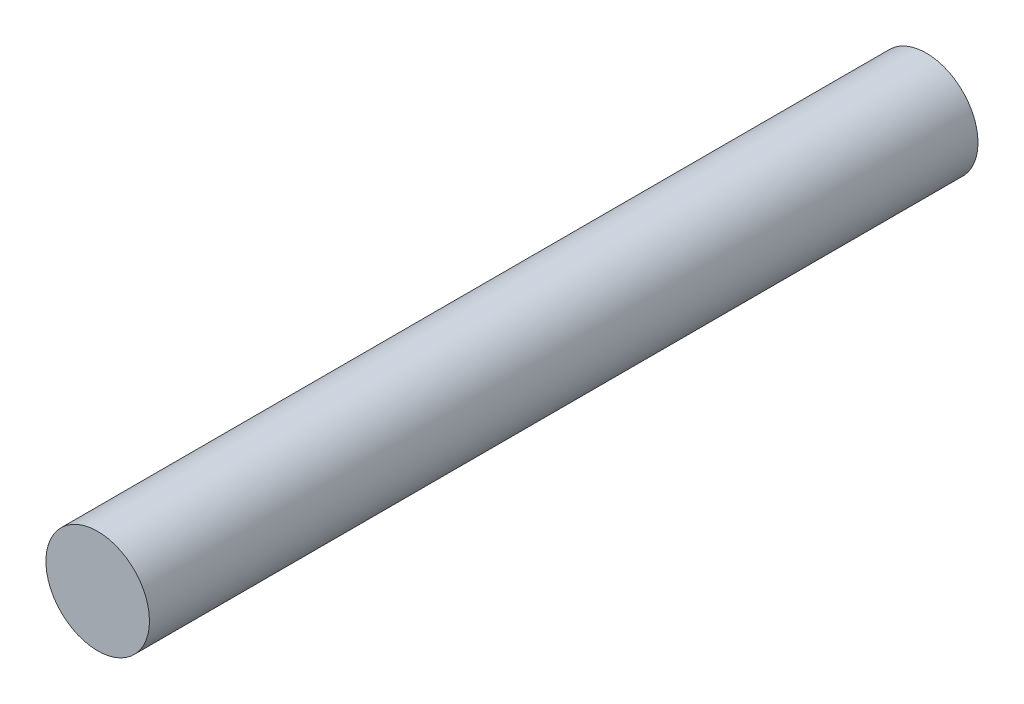
SolidWorks part; units mm, degrees
ref_plane "Front Plane" through (0, 0, 0) normal (0, 0, 1) x (1, 0, 0)
ref_plane "Top Plane" through (0, 0, 0) normal (0, 1, 0) x (1, 0, 0)
ref_plane "Right Plane" through (0, 0, 0) normal (1, 0, 0) x (0, 0, -1)
sketch "Sketch1" plane through (0, 0, 0) normal (0, 0, 1) x (1, 0, 0)
  circle A0 centre (0, 0) radius 3.175
  dimension "D1" = 6.35
extrude "Boss-Extrude1" add sketch "Sketch1" along normal blind 50.8 contours A0
